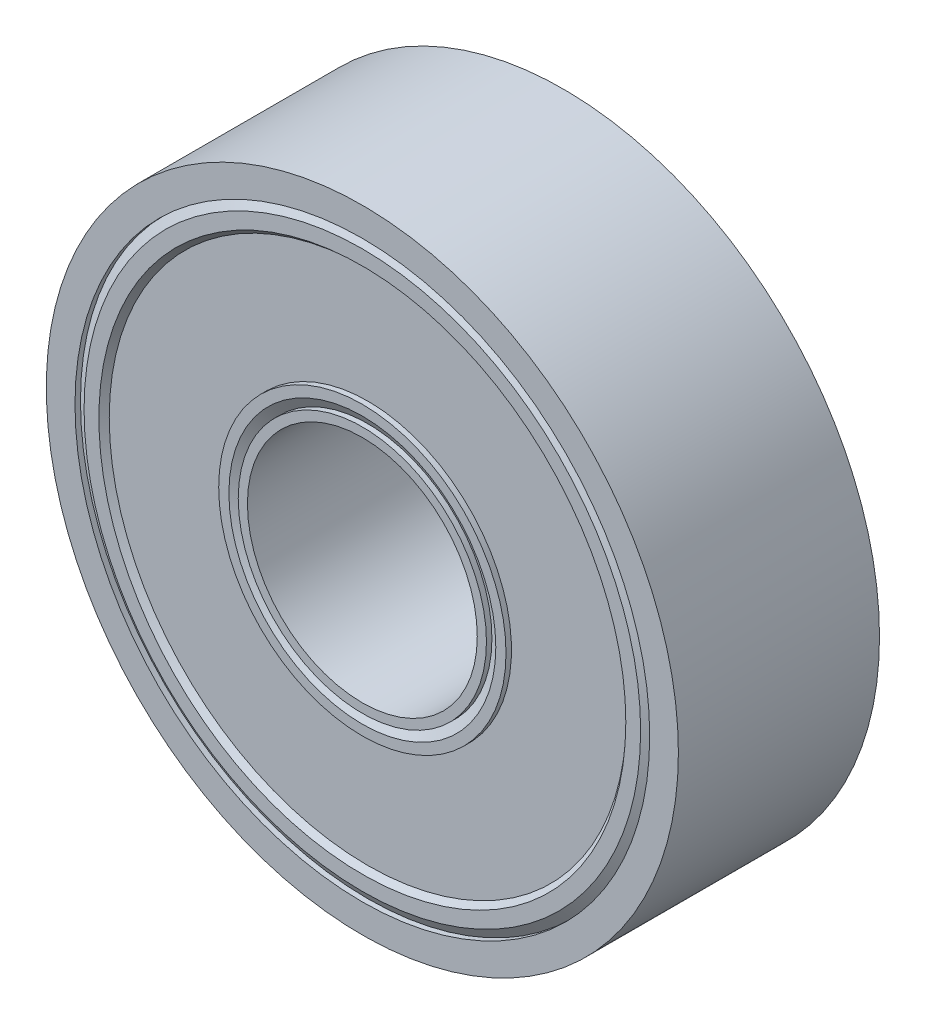
SolidWorks part; units mm, degrees
ref_plane "Front Plane" through (0, 0, 0) normal (0, 0, 1) x (1, 0, 0)
ref_plane "Top Plane" through (0, 0, 0) normal (0, 1, 0) x (1, 0, 0)
ref_plane "Right Plane" through (0, 0, 0) normal (1, 0, 0) x (0, 0, -1)
sketch "Sketch1" plane through (0, 0, 0) normal (0, 0, 1) x (1, 0, 0)
  circle A0 centre (0, 0) radius 11
  circle A1 centre (0, 0) radius 4
  dimension "D1" = 22
  dimension "D2" = 8
extrude "Boss-Extrude1" add sketch "Sketch1" along normal blind 7
sketch "Sketch2" plane through (0, 0, 0) normal (0, 1, 0) x (1, 0, 0)
  line L0 (0, 0) -> (0, -2.8034) construction
  line L3 (-9, -6.8094) -> (-5, -6.8094)
  line L4 (-5, -7.0594) -> (-5, -6.8094)
  line L6 (-9, -6.8094) -> (-9.3506, -7.2024)
  line L7 (-9.3506, -7.2024) -> (-10.0015, -6.8094)
  line L8 (-10.0015, -6.8094) -> (-10.0015, -7.3094)
  line L9 (-10.0015, -7.3094) -> (-10.9914, -7.3094)
  line L10 (-10.9914, -7.3094) -> (-10.9914, -9.2906)
  line L11 (-10.9914, -9.2906) -> (0, -9.2906)
  line L12 (0, -9.2906) -> (0, -7)
  line L13 (-11, -7) -> (11, -7) construction
  line L14 (0, -7) -> (-4.3197, -7)
  line L15 (-4.3197, -7) -> (-4.3197, -6.8094)
  line L16 (-4.3197, -6.8094) -> (-4.6452, -7)
  line L17 (-4.6452, -7) -> (-5, -7.0594)
  line L18 (-11, -3.5) -> (-10.0015, -3.5) construction
  line L20 (-4.6452, 0) -> (-5, 0.0594)
  line L21 (-4.3197, -0.1906) -> (-4.6452, 0)
  line L22 (-4.3197, 0) -> (-4.3197, -0.1906)
  line L23 (0, 0) -> (-4.3197, 0)
  line L24 (0, 2.2906) -> (0, 0)
  line L25 (-10.9914, 2.2906) -> (0, 2.2906)
  line L26 (-10.9914, 0.3094) -> (-10.9914, 2.2906)
  line L27 (-10.0015, 0.3094) -> (-10.9914, 0.3094)
  line L28 (-10.0015, -0.1906) -> (-10.0015, 0.3094)
  line L29 (-9.3506, 0.2024) -> (-10.0015, -0.1906)
  line L30 (-9, -0.1906) -> (-9.3506, 0.2024)
  line L31 (-5, 0.0594) -> (-5, -0.1906)
  line L32 (-9, -0.1906) -> (-5, -0.1906)
  dimension "D2" = 5
revolve "Cut-Revolve1" cut sketch "Sketch2" angle 360 about L0
